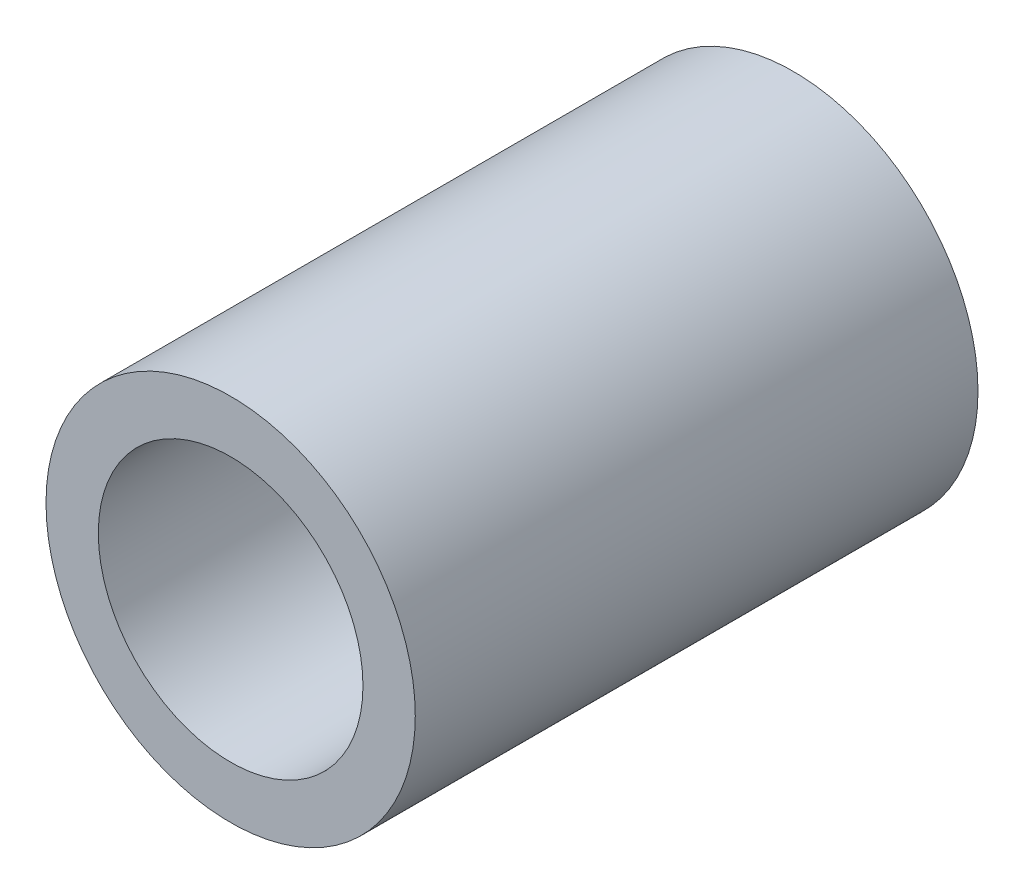
SolidWorks part; units mm, degrees
ref_plane "前视基准面" through (0, 0, 0) normal (0, 0, 1) x (1, 0, 0)
ref_plane "上视基准面" through (0, 0, 0) normal (0, 1, 0) x (1, 0, 0)
ref_plane "右视基准面" through (0, 0, 0) normal (1, 0, 0) x (0, 0, -1)
sketch "草图1" plane through (0, 0, 0) normal (0, 0, 1) x (1, 0, 0)
  circle A0 centre (0, 0) radius 10.5
  circle A1 centre (0, 0) radius 4.5
  dimension "D1" = 21
  dimension "D2" = 9
extrude "凸台-拉伸1" add sketch "草图1" along normal blind 2
sketch "草图2" plane through (0, 0, 2) normal (0, 0, 1) x (1, 0, 0)
  circle A0 centre (0, 0) radius 10.5
  circle A1 centre (0, 0) radius 7.525
  dimension "D1" = 15.05
  dimension "D2" = 21
extrude "凸台-拉伸2" add sketch "草图2" along normal blind 15
sketch "草图3" plane through (0, 0, 0) normal (0, 0, -1) x (-1, 0, 0)
  circle A0 centre (0, 0) radius 10.5
  circle A1 centre (0, 0) radius 7.525
  dimension "D1" = 15.05
  dimension "D2" = 21
extrude "凸台-拉伸3" add sketch "草图3" along normal blind 15
